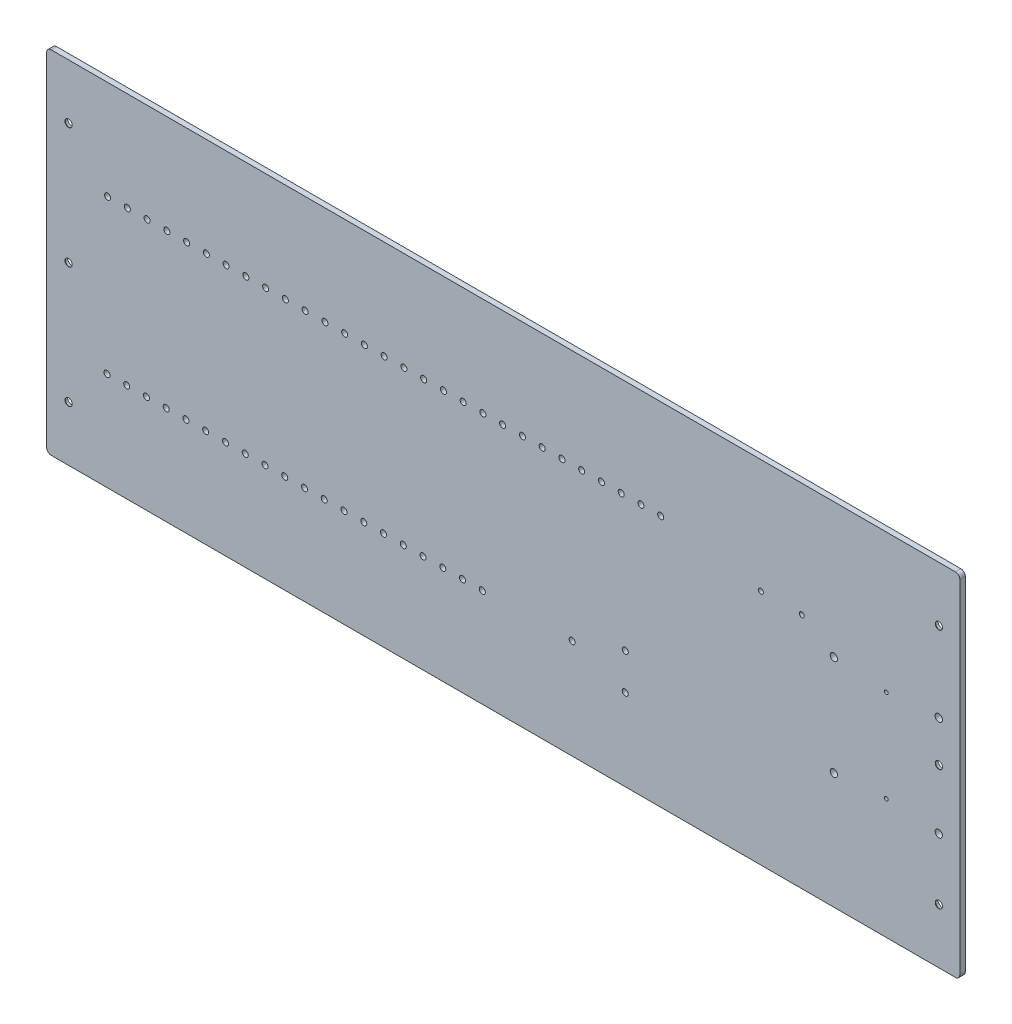
SolidWorks part; units mm, degrees
ref_plane "Front Plane" through (0, 0, 0) normal (0, 0, 1) x (1, 0, 0)
ref_plane "Top Plane" through (0, 0, 0) normal (0, 1, 0) x (1, 0, 0)
ref_plane "Right Plane" through (0, 0, 0) normal (1, 0, 0) x (0, 0, -1)
sketch "Sketch1" plane through (0, 0, 0) normal (0, 0, 1) x (1, 0, 0)
  line L1 (-412, -160) -> (412, -160)
  line L2 (-416, -156) -> (-416, 156)
  line L3 (-412, 160) -> (412, 160)
  line L4 (416, -156) -> (416, 156)
  line L5 (-416, -160) -> (416, 160) construction
  line L6 (-416, 160) -> (416, -160) construction
  arc A0 (416, 156) -> (412, 160) centre (412, 156) ccw
  arc A1 (416, -156) -> (412, -160) centre (412, -156) cw
  arc A2 (-412, -160) -> (-416, -156) centre (-412, -156) cw
  arc A3 (-416, 156) -> (-412, 160) centre (-412, 156) cw
  point P0 (0, 0)
  dimension "D3" = 4
  dimension "D1" = 320
  dimension "D2" = 832
extrude "Boss-Extrude1" add sketch "Sketch1" along normal blind 5
hole_wizard "M6 Clearance Hole1" positions "Sketch3" profile "Sketch2" hole size "M6" standard "ANSI Metric" end condition through all
sketch "Sketch3" plane through (0, 0, 0) normal (0, 0, -1) x (-1, 0, 0)
  line L0 (412, -160) -> (-412, -160) construction
  line L1 (-412, 160) -> (412, 160) construction
  point P0 (-396.9342, 110)
  point P2 (-396.9342, 0)
  point P4 (-396.9342, -110)
  dimension "D1" = 50
  dimension "D2" = 50
sketch "Sketch2" plane through (396.9342, 110, 0) normal (1, 0, 0) x (0, 1, 0)
  line L0 (0, 0) -> (0, 5)
  line L1 (0, 5) -> (3.3, 5)
  line L2 (3.3, 5) -> (3.3, 0)
  line L5 (3.3, 0) -> (0, 0)
  line L11 (0, -6.35) -> (0, 107.95) construction
  dimension "Thru Hole Dia." = 6.6
  dimension "Thru Hole Depth" = 5
pattern_linear "LPattern1" count 2 spacing 793 along (-1, 0, 0) of "M6 Clearance Hole1"
hole_wizard "CBORE for M6 Pan Head Machine Screw1" positions "Sketch5" profile "Sketch4" counterbore size "M6" standard "ANSI Metric" end condition through all
sketch "Sketch5" plane through (0, 0, 0) normal (0, 0, 1) x (1, 0, 0)
  point P0 (-396.0658, 110)
  point P3 (-396.0658, 0)
  point P6 (-396.0658, -110)
  point P9 (396.9342, 110)
  point P12 (396.9342, 0)
  point P15 (396.9342, -110)
sketch "Sketch4" plane through (-396.0658, 110, 0) normal (1, 0, 0) x (0, 1, 0)
  line L0 (0, 0) -> (0, 5)
  line L1 (0, 5) -> (3.3, 5)
  line L2 (3.3, 4.625) -> (3.3, 5)
  line L3 (3.3, 4.625) -> (3.325, 4.6)
  line L4 (3.325, 4.6) -> (6.5, 4.6)
  line L5 (6.5, 4.6) -> (6.5, 0)
  line L7 (0, 0) -> (6.5, 0)
  line L9 (-3.3, 4.625) -> (-3.325, 4.6) construction
  line L11 (0, -6.35) -> (0, 107.95) construction
  dimension "Thru Hole Dia." = 6.6
  dimension "Thru Hole Depth" = 5
  dimension "C'Bore Dia." = 13
  dimension "C'Bore Depth" = 4.6
  dimension "Mid C'Sink Dia." = 6.65
  dimension "Mid C'Sink Angle" = 90
hole_wizard "M5 Clearance Hole1" positions "Sketch7" profile "Sketch6" hole size "M5" standard "ANSI Metric" end condition through all
sketch "Sketch7" plane through (0, 0, 0) normal (0, 0, -1) x (-1, 0, 0)
  point P0 (361.0992, -70.2901)
sketch "Sketch6" plane through (-361.0992, -70.2901, 0) normal (1, 0, 0) x (0, 1, 0)
  line L0 (0, 0) -> (0, 5)
  line L1 (0, 5) -> (2.75, 5)
  line L2 (2.75, 5) -> (2.75, 0)
  line L5 (2.75, 0) -> (0, 0)
  line L11 (0, -6.35) -> (0, 107.95) construction
  dimension "Thru Hole Dia." = 5.5
  dimension "Thru Hole Depth" = 5
pattern_linear "LPattern2" count 20 spacing 18 along (1, 0, 0) of "M5 Clearance Hole1"
hole_wizard "M5 Clearance Hole2" positions "Sketch9" profile "Sketch8" hole size "M5" standard "ANSI Metric" end condition through all
sketch "Sketch9" plane through (0, 0, 0) normal (0, 0, -1) x (-1, 0, 0)
  point P0 (360.5188, 69.8986)
sketch "Sketch8" plane through (-360.5188, 69.8986, 0) normal (1, 0, 0) x (0, 1, 0)
  line L0 (0, 0) -> (0, 5)
  line L1 (0, 5) -> (2.75, 5)
  line L2 (2.75, 5) -> (2.75, 0)
  line L5 (2.75, 0) -> (0, 0)
  line L11 (0, -6.35) -> (0, 107.95) construction
  dimension "Thru Hole Dia." = 5.5
  dimension "Thru Hole Depth" = 5
pattern_linear "LPattern3" count 29 spacing 18 along (1, 0, 0) of "M5 Clearance Hole2"
hole_wizard "M5 Clearance Hole3" positions "Sketch11" profile "Sketch10" hole size "M5" standard "ANSI Metric" end condition through all
sketch "Sketch11" plane through (0, 0, 0) normal (0, 0, -1) x (-1, 0, 0)
  point P0 (-111.1657, -85.5849)
  point P3 (-111.1657, -52.5649)
  point P6 (-62.7787, -69.0749)
sketch "Sketch10" plane through (111.1657, -85.5849, 0) normal (1, 0, 0) x (0, 1, 0)
  line L0 (0, 0) -> (0, 5)
  line L1 (0, 5) -> (2.75, 5)
  line L2 (2.75, 5) -> (2.75, 0)
  line L5 (2.75, 0) -> (0, 0)
  line L11 (0, -6.35) -> (0, 107.95) construction
  dimension "Thru Hole Dia." = 5.5
  dimension "Thru Hole Depth" = 5
hole_wizard "M3 Clearance Hole1" positions "Sketch13" profile "Sketch12" hole size "M3" standard "ANSI Metric" end condition through all
sketch "Sketch13" plane through (0, 0, 0) normal (0, 0, -1) x (-1, 0, 0)
  point P0 (-349.0219, -50.4298)
  point P3 (-349.0219, 33.5702)
sketch "Sketch12" plane through (349.0219, -50.4298, 0) normal (1, 0, 0) x (0, 1, 0)
  line L0 (0, 0) -> (0, 5)
  line L1 (0, 5) -> (1.7, 5)
  line L2 (1.7, 5) -> (1.7, 0)
  line L5 (1.7, 0) -> (0, 0)
  line L11 (0, -6.35) -> (0, 107.95) construction
  dimension "Thru Hole Dia." = 3.4
  dimension "Thru Hole Depth" = 5
hole_wizard "M6 Clearance Hole2" positions "Sketch15" profile "Sketch14" hole size "M6" standard "ANSI Metric" end condition through all
sketch "Sketch15" plane through (0, 0, 0) normal (0, 0, -1) x (-1, 0, 0)
  point P0 (-301.2219, -54.1298)
  point P4 (-301.2219, 37.3702)
  point P7 (-396.8219, 37.2702)
  point P10 (-396.8219, -54.1298)
sketch "Sketch14" plane through (301.2219, -54.1298, 0) normal (1, 0, 0) x (0, 1, 0)
  line L0 (0, 0) -> (0, 5)
  line L1 (0, 5) -> (3.3, 5)
  line L2 (3.3, 5) -> (3.3, 0)
  line L5 (3.3, 0) -> (0, 0)
  line L11 (0, -6.35) -> (0, 107.95) construction
  dimension "Thru Hole Dia." = 6.6
  dimension "Thru Hole Depth" = 5
hole_wizard "M4 Clearance Hole1" positions "Sketch18" profile "Sketch16" hole size "M4" standard "ANSI Metric" end condition through all
sketch "Sketch18" plane through (0, 0, 0) normal (0, 0, -1) x (-1, 0, 0)
  point P0 (-234.7599, 56.1639)
  point P3 (-272.0072, 56.1639)
sketch "Sketch16" plane through (234.7599, 56.1639, 0) normal (1, 0, 0) x (0, 1, 0)
  line L0 (0, 0) -> (0, 5)
  line L1 (0, 5) -> (2.25, 5)
  line L2 (2.25, 5) -> (2.25, 0)
  line L5 (2.25, 0) -> (0, 0)
  line L11 (0, -6.35) -> (0, 107.95) construction
  dimension "Thru Hole Dia." = 4.5
  dimension "Thru Hole Depth" = 5
